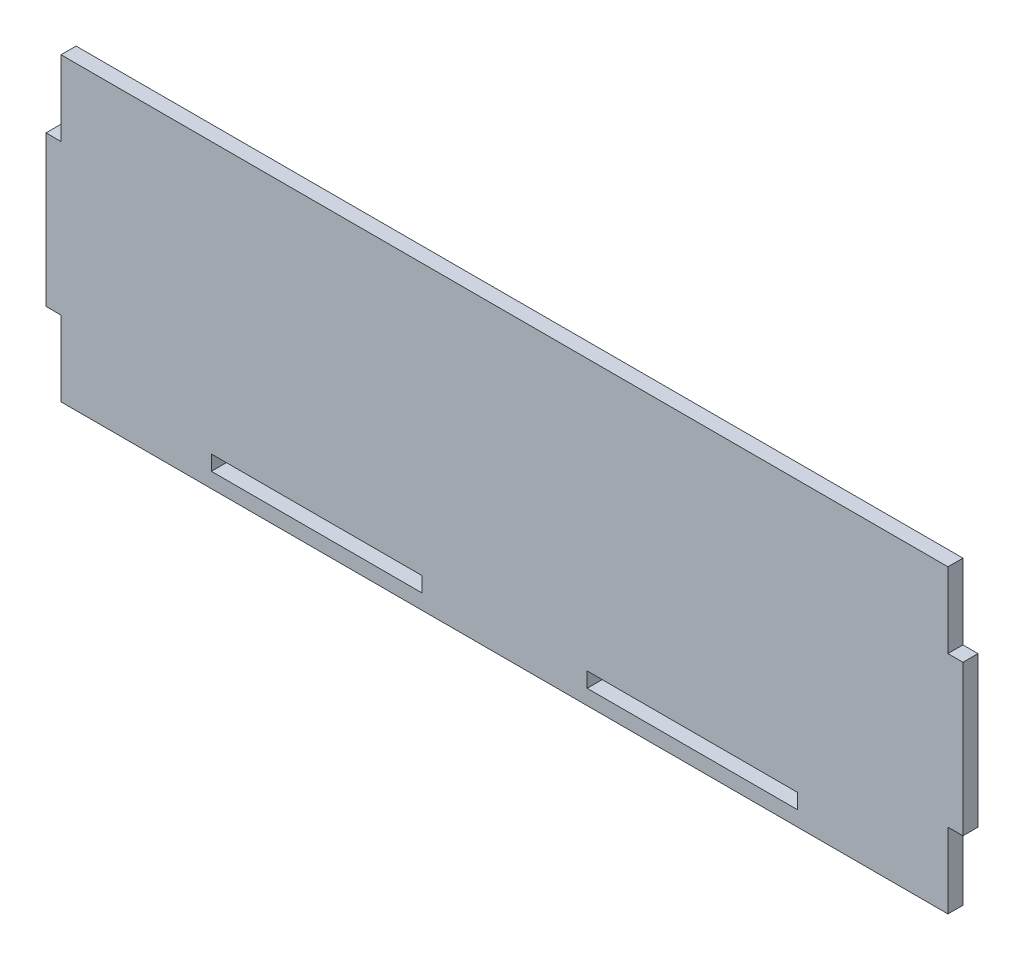
SolidWorks part; units mm, degrees
ref_plane "Front Plane" through (0, 0, 0) normal (0, 0, 1) x (1, 0, 0)
ref_plane "Top Plane" through (0, 0, 0) normal (0, 1, 0) x (1, 0, 0)
ref_plane "Right Plane" through (0, 0, 0) normal (1, 0, 0) x (0, 0, -1)
sketch "Sketch1" plane through (0, 0, 0) normal (0, 0, 1) x (1, 0, 0)
  line L0 (-147.5, 100) -> (-147.5, 154.3278) construction
  line L1 (0, 0) -> (-295, 0)
  line L2 (0, 0) -> (0, 100)
  line L3 (0, 100) -> (-295, 100)
  line L4 (-295, 0) -> (-295, 100)
  line L5 (0, 75) -> (5, 75)
  line L6 (0, 75) -> (0, 25)
  line L7 (0, 25) -> (5, 25)
  line L8 (5, 75) -> (5, 25)
  line L9 (-295, 25) -> (-300, 25)
  line L10 (-300, 75) -> (-300, 25)
  line L11 (-295, 75) -> (-300, 75)
  line L12 (-295, 75) -> (-295, 25)
  point P9 (5, 50)
  dimension "D1" = 295
  dimension "D2" = 100
  dimension "D3" = 5
  dimension "D4" = 50
  dimension "D5" = 50
extrude "Boss-Extrude1" add sketch "Sketch1" along normal blind 5 contours L4 L1 L2 L3 | L8 L5 L2 L7 | L4 L11 L10 L9
sketch "Sketch2" plane through (0, 0, 5) normal (0, 0, 1) x (1, 0, 0)
  line L0 (-295, 0) -> (-295, 25) construction
  line L1 (-245, 10) -> (-175, 10)
  line L2 (-245, 10) -> (-245, 5)
  line L3 (-245, 5) -> (-175, 5)
  line L4 (-175, 10) -> (-175, 5)
  line L5 (0, 0) -> (-295, 0) construction
  line L6 (-147.5, 0) -> (-147.5, 30.0626) construction
  line L7 (-120, 10) -> (-120, 5)
  line L8 (-50, 5) -> (-120, 5)
  line L9 (-50, 10) -> (-50, 5)
  line L10 (-50, 10) -> (-120, 10)
  dimension "D1" = 5
  dimension "D2" = 70
  dimension "D3" = 50
  dimension "D4" = 5
extrude "Cut-Extrude1" cut sketch "Sketch2" against normal blind 5
